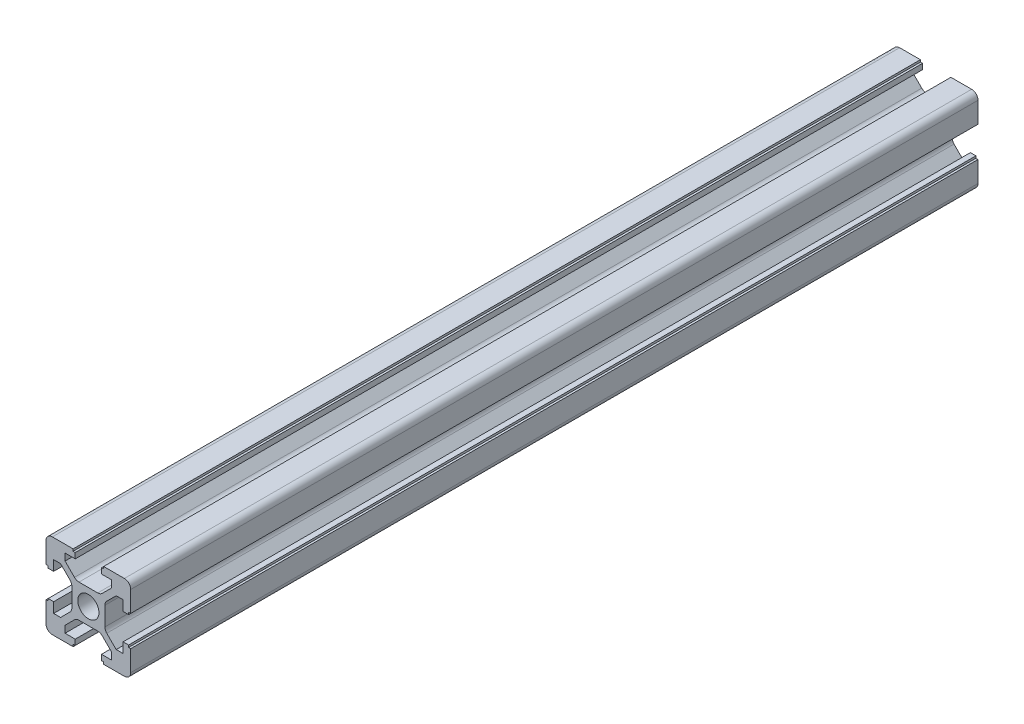
SolidWorks part; units mm, degrees
material "6061 合金"
ref_plane "前视基准面" through (0, 0, 0) normal (0, 0, 1) x (1, 0, 0)
ref_plane "上视基准面" through (0, 0, 0) normal (0, 1, 0) x (1, 0, 0)
ref_plane "右视基准面" through (0, 0, 0) normal (1, 0, 0) x (0, 0, -1)
sketch "草图1" plane through (0, 0, 0) normal (0, 0, 1) x (1, 0, 0)
  line L0 (-6.5607, 5.5) -> (-4.3393, 3.2787)
  line L1 (-3.9, 2.218) -> (-3.9, -2.218)
  line L2 (-4.3393, -3.2787) -> (-6.5607, -5.5)
  line L3 (-6.5607, -5.5) -> (-8.2, -5.5)
  line L4 (-8.2, -5.5) -> (-8.2, -3.1)
  line L5 (-8.2, -3.1) -> (-9.5, -3.1)
  line L6 (-9.5, -3.1) -> (-9.5, -3.6)
  line L7 (-9.5, -3.6) -> (-10, -3.6)
  line L8 (-10, -3.6) -> (-10, -8.5)
  line L9 (-6.5607, 5.5) -> (-8.2, 5.5)
  line L10 (-8.2, 5.5) -> (-8.2, 3.1)
  line L11 (-8.2, 3.1) -> (-9.5, 3.1)
  line L12 (-9.5, 3.1) -> (-9.5, 3.6)
  line L13 (-9.5, 3.6) -> (-10, 3.6)
  line L14 (-10, 3.6) -> (-10, 8.5)
  line L15 (5.5, 6.5607) -> (3.2787, 4.3393)
  line L16 (2.218, 3.9) -> (-2.218, 3.9)
  line L17 (-3.2787, 4.3393) -> (-5.5, 6.5607)
  line L18 (-5.5, 6.5607) -> (-5.5, 8.2)
  line L19 (-5.5, 8.2) -> (-3.1, 8.2)
  line L20 (-3.1, 8.2) -> (-3.1, 9.5)
  line L21 (-3.1, 9.5) -> (-3.6, 9.5)
  line L22 (-3.6, 9.5) -> (-3.6, 10)
  line L23 (-3.6, 10) -> (-8.5, 10)
  line L24 (5.5, 6.5607) -> (5.5, 8.2)
  line L25 (5.5, 8.2) -> (3.1, 8.2)
  line L26 (3.1, 8.2) -> (3.1, 9.5)
  line L27 (3.1, 9.5) -> (3.6, 9.5)
  line L28 (3.6, 9.5) -> (3.6, 10)
  line L29 (3.6, 10) -> (8.5, 10)
  line L30 (6.5607, -5.5) -> (4.3393, -3.2787)
  line L31 (3.9, -2.218) -> (3.9, 2.218)
  line L32 (4.3393, 3.2787) -> (6.5607, 5.5)
  line L33 (6.5607, 5.5) -> (8.2, 5.5)
  line L34 (8.2, 5.5) -> (8.2, 3.1)
  line L35 (8.2, 3.1) -> (9.5, 3.1)
  line L36 (9.5, 3.1) -> (9.5, 3.6)
  line L37 (9.5, 3.6) -> (10, 3.6)
  line L38 (10, 3.6) -> (10, 8.5)
  line L39 (6.5607, -5.5) -> (8.2, -5.5)
  line L40 (8.2, -5.5) -> (8.2, -3.1)
  line L41 (8.2, -3.1) -> (9.5, -3.1)
  line L42 (9.5, -3.1) -> (9.5, -3.6)
  line L43 (9.5, -3.6) -> (10, -3.6)
  line L44 (10, -3.6) -> (10, -8.5)
  line L45 (-5.5, -6.5607) -> (-3.2787, -4.3393)
  line L46 (-2.218, -3.9) -> (2.218, -3.9)
  line L47 (3.2787, -4.3393) -> (5.5, -6.5607)
  line L48 (5.5, -6.5607) -> (5.5, -8.2)
  line L49 (5.5, -8.2) -> (3.1, -8.2)
  line L50 (3.1, -8.2) -> (3.1, -9.5)
  line L51 (3.1, -9.5) -> (3.6, -9.5)
  line L52 (3.6, -9.5) -> (3.6, -10)
  line L53 (3.6, -10) -> (8.5, -10)
  line L54 (-5.5, -6.5607) -> (-5.5, -8.2)
  line L55 (-5.5, -8.2) -> (-3.1, -8.2)
  line L56 (-3.1, -8.2) -> (-3.1, -9.5)
  line L57 (-3.1, -9.5) -> (-3.6, -9.5)
  line L58 (-3.6, -9.5) -> (-3.6, -10)
  line L59 (-3.6, -10) -> (-8.5, -10)
  line L60 (0, 0) -> (-3.9, 2.8393) construction
  line L61 (0, 0) -> (2.8393, 3.9) construction
  arc A0 (4.3393, -3.2787) -> (3.9, -2.218) centre (5.4, -2.218) cw
  arc A1 (3.9, 2.218) -> (4.3393, 3.2787) centre (5.4, 2.218) cw
  arc A2 (3.2787, 4.3393) -> (2.218, 3.9) centre (2.218, 5.4) cw
  arc A3 (-2.218, 3.9) -> (-3.2787, 4.3393) centre (-2.218, 5.4) cw
  arc A4 (-4.3393, 3.2787) -> (-3.9, 2.218) centre (-5.4, 2.218) cw
  arc A5 (-3.9, -2.218) -> (-4.3393, -3.2787) centre (-5.4, -2.218) cw
  arc A6 (2.218, -3.9) -> (3.2787, -4.3393) centre (2.218, -5.4) cw
  arc A7 (-3.2787, -4.3393) -> (-2.218, -3.9) centre (-2.218, -5.4) cw
  arc A8 (-10, -8.5) -> (-8.5, -10) centre (-8.5, -8.5) ccw
  arc A9 (10, -8.5) -> (8.5, -10) centre (8.5, -8.5) cw
  arc A10 (8.5, 10) -> (10, 8.5) centre (8.5, 8.5) cw
  arc A11 (-10, 8.5) -> (-8.5, 10) centre (-8.5, 8.5) cw
  circle A12 centre (0, 0) radius 2.5
  point P27 (-3.9, 0)
  point P75 (2.8393, 3.9)
  dimension "D12" = 1.5
  dimension "D13" = 5
  dimension "D2" = 20
  dimension "D3" = 7.2
  dimension "D4" = 6.2
  dimension "D5" = 7.8
  dimension "D6" = 45
  dimension "D7" = 1.5
  dimension "D8" = 11
  dimension "D9" = 1.8
  dimension "D10" = 0.5
  dimension "D11" = 3.1
  dimension "D1" = 4
extrude "凸台-拉伸1" add sketch "草图1" along normal mid plane 200
